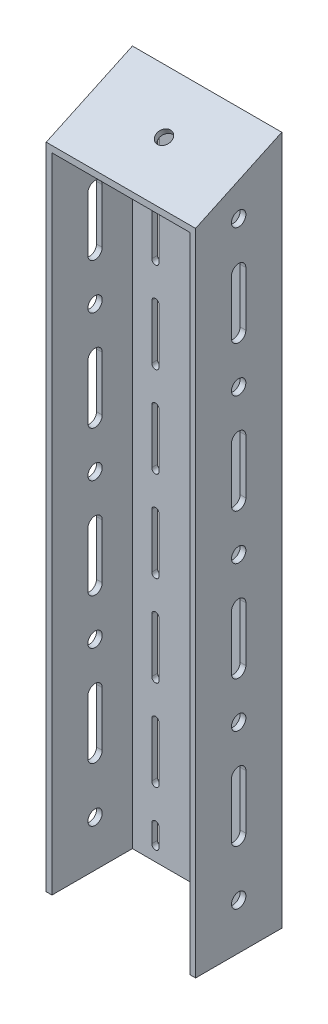
SolidWorks part; units mm, degrees
ref_plane "Front Plane" through (0, 0, 0) normal (0, 0, 1) x (1, 0, 0)
ref_plane "Top Plane" through (0, 0, 0) normal (0, 1, 0) x (1, 0, 0)
ref_plane "Right Plane" through (0, 0, 0) normal (1, 0, 0) x (0, 0, -1)
sketch "Sketch1" plane through (0, 0, 0) normal (0, 1, 0) x (1, 0, 0)
  line L0 (-38.1, 20.64) -> (38.1, 20.64)
  line L1 (-41.275, 23.815) -> (41.275, 23.815)
  line L2 (-41.275, 23.815) -> (-41.275, -23.815)
  line L3 (-41.275, -23.815) -> (-38.1, -23.815)
  line L4 (41.275, 23.815) -> (41.275, -23.815)
  line L5 (-41.275, 23.815) -> (41.275, -23.815) construction
  line L6 (-41.275, -23.815) -> (41.275, 23.815) construction
  line L7 (38.1, 20.64) -> (38.1, -23.815)
  line L9 (-38.1, 20.64) -> (-38.1, -23.815)
  line L10 (-38.1, 20.64) -> (-38.1, -20.64) construction
  line L11 (-38.1, -20.64) -> (38.1, -20.64) construction
  line L12 (38.1, 20.64) -> (38.1, -20.64) construction
  line L13 (38.1, -23.815) -> (41.275, -23.815)
  line L14 (-41.275, -23.815) -> (41.275, -23.815) construction
  point P0 (0, 0)
  dimension "D1" = 3.175
extrude "Boss-Extrude1" add sketch "Sketch1" along normal mid plane 381
sketch "Sketch2" plane through (0, 0, 0) normal (1, 0, 0) x (0, 0, -1)
  line L0 (-23.815, -190.5) -> (23.815, -190.5) construction
  line L1 (0, -135.1) -> (0, -105.1) construction
  line L2 (-3.9688, -135.1) -> (-3.9688, -105.1)
  line L3 (3.9688, -135.1) -> (3.9688, -105.1)
  line L4 (0, -54.85) -> (0, -24.85) construction
  line L5 (-3.9688, -54.85) -> (-3.9688, -24.85)
  line L6 (3.9688, -54.85) -> (3.9688, -24.85)
  line L7 (0, 25.4) -> (0, 55.4) construction
  line L8 (-3.9688, 25.4) -> (-3.9688, 55.4)
  line L9 (3.9688, 25.4) -> (3.9688, 55.4)
  line L10 (0, 105.65) -> (0, 135.65) construction
  line L11 (-3.9688, 105.65) -> (-3.9688, 135.65)
  line L12 (3.9688, 105.65) -> (3.9688, 135.65)
  circle A0 centre (0, -165.1) radius 3.9687
  arc A1 (-3.9688, -135.1) -> (3.9688, -135.1) centre (0, -135.1) ccw
  arc A2 (3.9688, -105.1) -> (-3.9688, -105.1) centre (0, -105.1) ccw
  circle A3 centre (0, -79.975) radius 3.9687
  arc A4 (-3.9688, -54.85) -> (3.9688, -54.85) centre (0, -54.85) ccw
  arc A5 (3.9688, -24.85) -> (-3.9688, -24.85) centre (0, -24.85) ccw
  arc A6 (-3.9688, 25.4) -> (3.9688, 25.4) centre (0, 25.4) ccw
  arc A7 (3.9688, 55.4) -> (-3.9688, 55.4) centre (0, 55.4) ccw
  arc A8 (-3.9688, 105.65) -> (3.9688, 105.65) centre (0, 105.65) ccw
  arc A9 (3.9688, 135.65) -> (-3.9688, 135.65) centre (0, 135.65) ccw
  circle A10 centre (0, 0.275) radius 3.9688
  circle A11 centre (0, 80.525) radius 3.9687
  circle A12 centre (0, 161.05) radius 3.9687
  point P7 (0, -120.1)
  point P16 (0, -39.85)
  point P21 (0, 40.4)
  point P30 (0, 120.65)
  dimension "D1" = 25.4
  dimension "D2" = 30
  dimension "D4" = 30
  dimension "D5" = 50.25
  dimension "D8" = 25.125
  dimension "D9" = 25.125
  dimension "D10" = 25.125
  dimension "D13" = 25.4
  dimension "D3" = 30
  dimension "D6" = 50.25
  dimension "D7" = 50.25
  dimension "D11" = 30
  dimension "D12" = 30
extrude "Cut-Extrude1" cut sketch "Sketch2" against normal mid plane 381
sketch "Sketch3" plane through (0, 0, -23.815) normal (0, 0, -1) x (-1, 0, 0)
  line L0 (0, -178) -> (0, -148) construction
  line L1 (-1.9844, -178) -> (-1.9844, -148)
  line L2 (1.9844, -178) -> (1.9844, -148)
  line L3 (-41.275, -190.5) -> (41.275, -190.5) construction
  line L4 (0, -128) -> (0, -98) construction
  line L5 (-1.9844, -128) -> (-1.9844, -98)
  line L6 (1.9844, -128) -> (1.9844, -98)
  line L7 (0, -78) -> (0, -48) construction
  line L8 (-1.9844, -78) -> (-1.9844, -48)
  line L9 (1.9844, -78) -> (1.9844, -48)
  line L10 (0, -28) -> (0, 2) construction
  line L11 (-1.9844, -28) -> (-1.9844, 2)
  line L12 (1.9844, -28) -> (1.9844, 2)
  line L13 (0, 22) -> (0, 52) construction
  line L14 (-1.9844, 22) -> (-1.9844, 52)
  line L15 (1.9844, 22) -> (1.9844, 52)
  line L16 (0, 72) -> (0, 102) construction
  line L17 (-1.9844, 72) -> (-1.9844, 102)
  line L18 (1.9844, 72) -> (1.9844, 102)
  line L19 (0, 122) -> (0, 152) construction
  line L20 (-1.9844, 122) -> (-1.9844, 152)
  line L21 (1.9844, 122) -> (1.9844, 152)
  line L22 (25.4, -152.78) -> (25.4, -122.78) construction
  line L23 (23.4156, -152.78) -> (23.4156, -122.78)
  line L24 (27.3844, -152.78) -> (27.3844, -122.78)
  line L25 (25.4, -102.78) -> (25.4, -72.78) construction
  line L26 (23.4156, -102.78) -> (23.4156, -72.78)
  line L27 (27.3844, -102.78) -> (27.3844, -72.78)
  line L28 (25.4, -52.78) -> (25.4, -22.78) construction
  line L29 (23.4156, -52.78) -> (23.4156, -22.78)
  line L30 (27.3844, -52.78) -> (27.3844, -22.78)
  line L31 (25.4, -2.78) -> (25.4, 27.22) construction
  line L32 (23.4156, -2.78) -> (23.4156, 27.22)
  line L33 (27.3844, -2.78) -> (27.3844, 27.22)
  line L34 (25.4, 47.22) -> (25.4, 77.22) construction
  line L35 (23.4156, 47.22) -> (23.4156, 77.22)
  line L36 (27.3844, 47.22) -> (27.3844, 77.22)
  line L37 (25.4, 97.22) -> (25.4, 127.22) construction
  line L38 (23.4156, 97.22) -> (23.4156, 127.22)
  line L39 (27.3844, 97.22) -> (27.3844, 127.22)
  line L40 (25.4, 147.22) -> (25.4, 177.22) construction
  line L41 (23.4156, 147.22) -> (23.4156, 177.22)
  line L42 (27.3844, 147.22) -> (27.3844, 177.22)
  line L43 (-25.4, -152.78) -> (-25.4, -122.78) construction
  line L44 (-27.3844, -152.78) -> (-27.3844, -122.78)
  line L45 (-23.4156, -152.78) -> (-23.4156, -122.78)
  line L46 (-25.4, -102.78) -> (-25.4, -72.78) construction
  line L47 (-27.3844, -102.78) -> (-27.3844, -72.78)
  line L48 (-23.4156, -102.78) -> (-23.4156, -72.78)
  line L49 (-25.4, -52.78) -> (-25.4, -22.78) construction
  line L50 (-27.3844, -52.78) -> (-27.3844, -22.78)
  line L51 (-23.4156, -52.78) -> (-23.4156, -22.78)
  line L52 (-25.4, -2.78) -> (-25.4, 27.22) construction
  line L53 (-27.3844, -2.78) -> (-27.3844, 27.22)
  line L54 (-23.4156, -2.78) -> (-23.4156, 27.22)
  line L55 (-25.4, 47.22) -> (-25.4, 77.22) construction
  line L56 (-27.3844, 47.22) -> (-27.3844, 77.22)
  line L57 (-23.4156, 47.22) -> (-23.4156, 77.22)
  line L58 (-25.4, 97.22) -> (-25.4, 127.22) construction
  line L59 (-27.3844, 97.22) -> (-27.3844, 127.22)
  line L60 (-23.4156, 97.22) -> (-23.4156, 127.22)
  line L61 (-25.4, 147.22) -> (-25.4, 177.22) construction
  line L62 (-27.3844, 147.22) -> (-27.3844, 177.22)
  line L63 (-23.4156, 147.22) -> (-23.4156, 177.22)
  line L64 (25.4, -172.78) -> (25.4, -182.78) construction
  line L65 (27.3844, -172.78) -> (27.3844, -182.78)
  line L66 (23.4156, -172.78) -> (23.4156, -182.78)
  line L67 (-25.4, -172.78) -> (-25.4, -182.78) construction
  line L68 (-23.4156, -172.78) -> (-23.4156, -182.78)
  line L69 (-27.3844, -172.78) -> (-27.3844, -182.78)
  arc A0 (-1.9844, -178) -> (1.9844, -178) centre (0, -178) ccw
  arc A1 (1.9844, -148) -> (-1.9844, -148) centre (0, -148) ccw
  arc A2 (-1.9844, -128) -> (1.9844, -128) centre (0, -128) ccw
  arc A3 (1.9844, -98) -> (-1.9844, -98) centre (0, -98) ccw
  arc A4 (-1.9844, -78) -> (1.9844, -78) centre (0, -78) ccw
  arc A5 (1.9844, -48) -> (-1.9844, -48) centre (0, -48) ccw
  arc A6 (-1.9844, -28) -> (1.9844, -28) centre (0, -28) ccw
  arc A7 (1.9844, 2) -> (-1.9844, 2) centre (0, 2) ccw
  arc A8 (-1.9844, 22) -> (1.9844, 22) centre (0, 22) ccw
  arc A9 (1.9844, 52) -> (-1.9844, 52) centre (0, 52) ccw
  arc A10 (-1.9844, 72) -> (1.9844, 72) centre (0, 72) ccw
  arc A11 (1.9844, 102) -> (-1.9844, 102) centre (0, 102) ccw
  arc A12 (-1.9844, 122) -> (1.9844, 122) centre (0, 122) ccw
  arc A13 (1.9844, 152) -> (-1.9844, 152) centre (0, 152) ccw
  arc A14 (23.4156, -152.78) -> (27.3844, -152.78) centre (25.4, -152.78) ccw
  arc A15 (27.3844, -122.78) -> (23.4156, -122.78) centre (25.4, -122.78) ccw
  arc A16 (23.4156, -102.78) -> (27.3844, -102.78) centre (25.4, -102.78) ccw
  arc A17 (27.3844, -72.78) -> (23.4156, -72.78) centre (25.4, -72.78) ccw
  arc A18 (23.4156, -52.78) -> (27.3844, -52.78) centre (25.4, -52.78) ccw
  arc A19 (27.3844, -22.78) -> (23.4156, -22.78) centre (25.4, -22.78) ccw
  arc A20 (23.4156, -2.78) -> (27.3844, -2.78) centre (25.4, -2.78) ccw
  arc A21 (27.3844, 27.22) -> (23.4156, 27.22) centre (25.4, 27.22) ccw
  arc A22 (23.4156, 47.22) -> (27.3844, 47.22) centre (25.4, 47.22) ccw
  arc A23 (27.3844, 77.22) -> (23.4156, 77.22) centre (25.4, 77.22) ccw
  arc A24 (23.4156, 97.22) -> (27.3844, 97.22) centre (25.4, 97.22) ccw
  arc A25 (27.3844, 127.22) -> (23.4156, 127.22) centre (25.4, 127.22) ccw
  arc A26 (23.4156, 147.22) -> (27.3844, 147.22) centre (25.4, 147.22) ccw
  arc A27 (27.3844, 177.22) -> (23.4156, 177.22) centre (25.4, 177.22) ccw
  arc A28 (-27.3844, -152.78) -> (-23.4156, -152.78) centre (-25.4, -152.78) ccw
  arc A29 (-23.4156, -122.78) -> (-27.3844, -122.78) centre (-25.4, -122.78) ccw
  arc A30 (-27.3844, -102.78) -> (-23.4156, -102.78) centre (-25.4, -102.78) ccw
  arc A31 (-23.4156, -72.78) -> (-27.3844, -72.78) centre (-25.4, -72.78) ccw
  arc A32 (-27.3844, -52.78) -> (-23.4156, -52.78) centre (-25.4, -52.78) ccw
  arc A33 (-23.4156, -22.78) -> (-27.3844, -22.78) centre (-25.4, -22.78) ccw
  arc A34 (-27.3844, -2.78) -> (-23.4156, -2.78) centre (-25.4, -2.78) ccw
  arc A35 (-23.4156, 27.22) -> (-27.3844, 27.22) centre (-25.4, 27.22) ccw
  arc A36 (-27.3844, 47.22) -> (-23.4156, 47.22) centre (-25.4, 47.22) ccw
  arc A37 (-23.4156, 77.22) -> (-27.3844, 77.22) centre (-25.4, 77.22) ccw
  arc A38 (-27.3844, 97.22) -> (-23.4156, 97.22) centre (-25.4, 97.22) ccw
  arc A39 (-23.4156, 127.22) -> (-27.3844, 127.22) centre (-25.4, 127.22) ccw
  arc A40 (-27.3844, 147.22) -> (-23.4156, 147.22) centre (-25.4, 147.22) ccw
  arc A41 (-23.4156, 177.22) -> (-27.3844, 177.22) centre (-25.4, 177.22) ccw
  arc A42 (27.3844, -172.78) -> (23.4156, -172.78) centre (25.4, -172.78) ccw
  arc A43 (23.4156, -182.78) -> (27.3844, -182.78) centre (25.4, -182.78) ccw
  arc A44 (-23.4156, -172.78) -> (-27.3844, -172.78) centre (-25.4, -172.78) ccw
  arc A45 (-27.3844, -182.78) -> (-23.4156, -182.78) centre (-25.4, -182.78) ccw
  point P3 (0, -163)
  point P14 (0, -113)
  point P21 (0, -63)
  point P28 (0, -13)
  point P35 (0, 37)
  point P42 (0, 87)
  point P49 (0, 137)
  point P56 (25.4, -137.78)
  point P65 (25.4, -87.78)
  point P72 (25.4, -37.78)
  point P79 (25.4, 12.22)
  point P86 (25.4, 62.22)
  point P93 (25.4, 112.22)
  point P100 (25.4, 162.22)
  point P106 (-25.4, -137.78)
  point P115 (-25.4, -87.78)
  point P122 (-25.4, -37.78)
  point P129 (-25.4, 12.22)
  point P136 (-25.4, 62.22)
  point P143 (-25.4, 112.22)
  point P150 (-25.4, 162.22)
  point P156 (25.4, -177.78)
  point P164 (-25.4, -177.78)
  dimension "D1" = 12.5
  dimension "D4" = 7
  dimension "D5" = 7
  dimension "D6" = 10
  dimension "D2" = 30
  dimension "D3" = 7
extrude "Cut-Extrude2" cut sketch "Sketch3" against normal blind 10
sketch "Sketch4" plane through (0, 0, 0) normal (1, 0, 0) x (0, 0, -1)
  line L0 (-23.815, 190.5) -> (23.815, 190.5)
  line L1 (23.815, 190.5) -> (-23.815, 168.2898)
  line L2 (91.2146, -315.9667) -> (158.2814, -284.693) construction
  line L3 (-23.815, 190.5) -> (-23.815, 168.2898)
  line L4 (-23.815, 190.5) -> (-23.815, -190.5) construction
extrude "Cut-Extrude3" cut sketch "Sketch4" against normal mid plane 200
sketch "Sketch6" plane through (0, 0, 0) normal (1, 0, 0) x (0, 0, -1)
  line L1 (23.815, 190.5) -> (-23.815, 168.2898) construction
  line L2 (25.1568, 187.6225) -> (-22.4732, 165.4122)
  line L3 (20.64, 185.5162) -> (-23.815, 164.7865)
  line L4 (20.64, 189.0195) -> (-23.815, 168.2898)
  line L5 (-23.815, 168.2898) -> (-23.815, 164.7865)
  line L7 (20.64, 189.0195) -> (20.64, 185.5162)
  line L8 (20.64, 189.0195) -> (20.64, -190.5) construction
  dimension "D1" = 3.175
extrude "Boss-Extrude3" add sketch "Sketch6" against normal up to body
mirror "Mirror1" about plane through (0, 0, 0) normal (1, 0, 0) of "Boss-Extrude3"
sketch "Sketch7" plane through (0, 147.3538, 68.7122) normal (0, 0.9063, 0.4226) x (1, 0, 0)
  line L0 (-41.275, 102.0925) -> (41.275, 49.5386) construction
  line L1 (-41.275, 49.5386) -> (41.275, 49.5386) construction
  line L2 (41.275, 49.5386) -> (41.275, -102.0925) construction
  circle A0 centre (0, 75.8156) radius 3.9687
extrude "Cut-Extrude4" cut sketch "Sketch7" against normal mid plane 10
